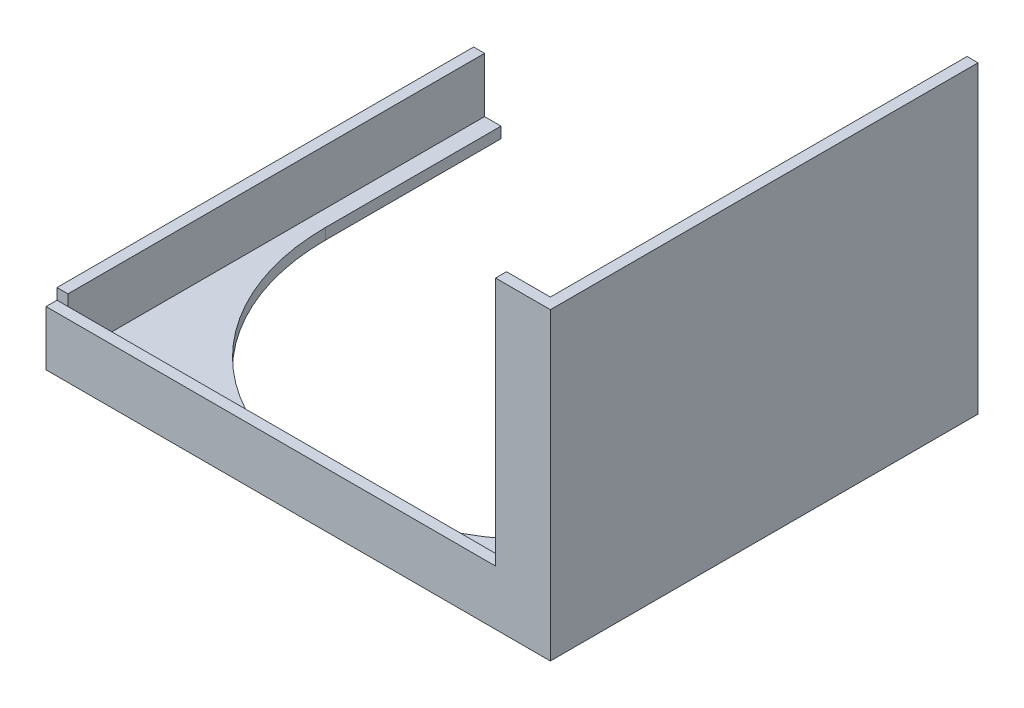
SolidWorks part; units mm, degrees
ref_plane "前视基准面" through (0, 0, 0) normal (0, 0, 1) x (1, 0, 0)
ref_plane "上视基准面" through (0, 0, 0) normal (0, 1, 0) x (1, 0, 0)
ref_plane "右视基准面" through (0, 0, 0) normal (1, 0, 0) x (0, 0, -1)
sketch "草图1" plane through (0, 0, 0) normal (0, 0, 1) x (1, 0, 0)
  line L0 (-92, 0) -> (0, 0)
  line L1 (0, 0) -> (0, 55.5)
  line L2 (0, 55.5) -> (-2, 55.5)
  line L3 (-2, 55.5) -> (-2, 2)
  line L4 (-2, 2) -> (-92, 2)
  line L5 (-92, 2) -> (-92, 0)
  dimension "D1" = 2
  dimension "D2" = 2
  dimension "D3" = 92
  dimension "D4" = 55.5
extrude "凸台-拉伸1" add sketch "草图1" along normal blind 76
sketch "草图3" plane through (0, 0, 76) normal (0, 0, 1) x (1, 0, 0)
  line L0 (0, 55.5) -> (-10, 55.5)
  line L1 (-10, 55.5) -> (-10, 10)
  line L2 (-10, 10) -> (-92, 10)
  line L3 (-92, 10) -> (-92, 0)
  line L4 (-92, 0) -> (0, 0)
  line L5 (0, 0) -> (0, 55.5)
  dimension "D1" = 10
  dimension "D2" = 10
extrude "凸台-拉伸2" add sketch "草图3" along normal blind 2
sketch "草图4" plane through (0, 0, 0) normal (0, -1, 0) x (1, 0, 0)
  line L0 (-46, 0) -> (-46, 81.0193) construction
  line L1 (-92, 0) -> (0, 0) construction
  line L2 (-87, 0) -> (-87, 32)
  line L3 (-92, 78) -> (0, 78) construction
  line L4 (-5, 0) -> (-5, 32)
  line L5 (-87, 0) -> (-5, 0)
  arc A0 (-87, 32) -> (-5, 32) centre (-46, 32) cw
  dimension "D1" = 41
  dimension "D2" = 46
extrude "切除-拉伸1" cut sketch "草图4" against normal blind 10
sketch "草图5" plane through (0, 2, 0) normal (0, 1, 0) x (1, 0, 0)
  line L1 (-92, -76) -> (-90, -76)
  line L2 (-92, -76) -> (-92, 0)
  line L3 (-92, 0) -> (-90, 0)
  line L4 (-90, -76) -> (-90, 0)
  point P7 (-89.125, 0)
  dimension "D1" = 2
extrude "凸台-拉伸3" add sketch "草图5" along normal blind 10
